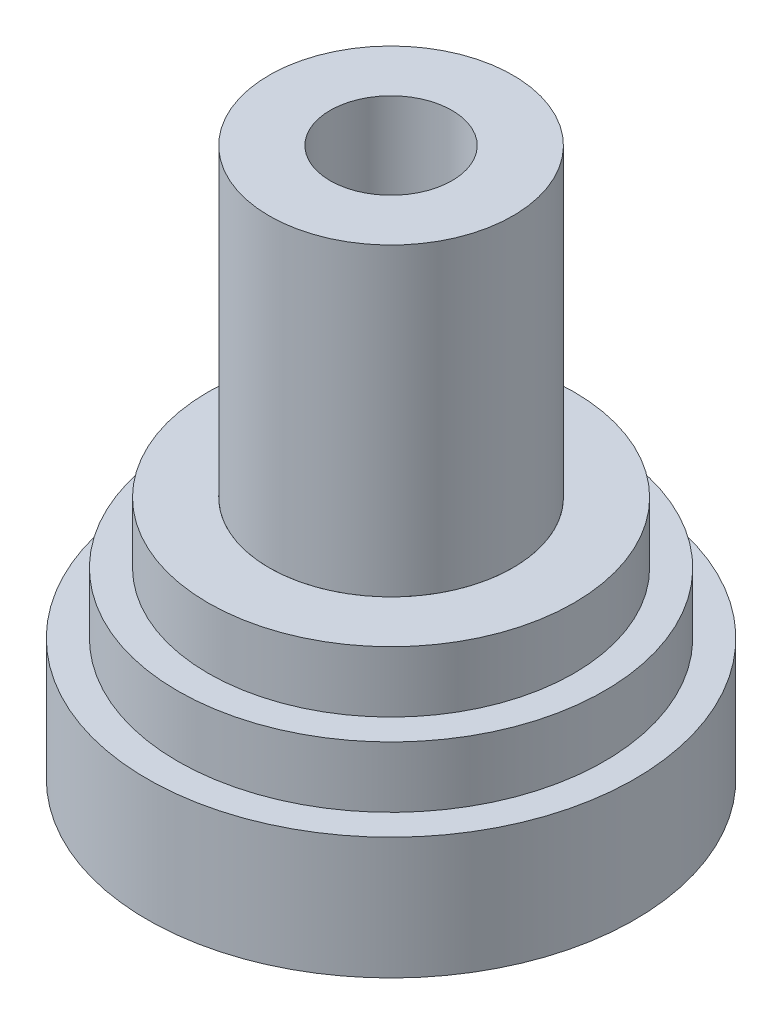
SolidWorks part; units mm, degrees
ref_plane "Front Plane" through (0, 0, 0) normal (0, 0, 1) x (1, 0, 0)
ref_plane "Top Plane" through (0, 0, 0) normal (0, 1, 0) x (1, 0, 0)
ref_plane "Right Plane" through (0, 0, 0) normal (1, 0, 0) x (0, 0, -1)
sketch "Sketch1" plane through (0, 0, 0) normal (0, 1, 0) x (1, 0, 0)
  circle A0 centre (0, 0) radius 20
  dimension "D1" = 40
extrude "Boss-Extrude1" add sketch "Sketch1" along normal blind 50
sketch "Sketch2" plane through (0, 50, 0) normal (0, 1, 0) x (1, 0, 0)
  circle A0 centre (0, 0) radius 10
  circle A1 centre (0, 0) radius 20 construction
  dimension "D1" = 10
extrude "Cut-Extrude1" cut sketch "Sketch2" against normal blind 50
sketch "Sketch4" plane through (0, 0, 0) normal (1, 0, 0) x (0, 0, -1)
  line L1 (30, 0) -> (30, -10)
  line L2 (30, -10) -> (35, -10)
  line L3 (35, -10) -> (35, -20)
  line L4 (35, -20) -> (40, -20)
  line L5 (40, -20) -> (40, -40)
  line L6 (40, -40) -> (30, -40)
  line L7 (30, -40) -> (30, -15)
  line L10 (0, 0) -> (0, 16.4388) construction
  line L11 (20, 0) -> (30, 0)
  line L12 (30, -15) -> (20, -15)
  line L13 (20, -15) -> (20, 0)
  dimension "D2" = 15
  dimension "D3" = 25
  dimension "D4" = 10
  dimension "D5" = 20
  dimension "D6" = 10
  dimension "D7" = 5
  dimension "D8" = 5
  dimension "D9" = 30
  dimension "D10" = 10
  dimension "D11" = 40
revolve "Revolve1" add sketch "Sketch4" angle 360 about L10
